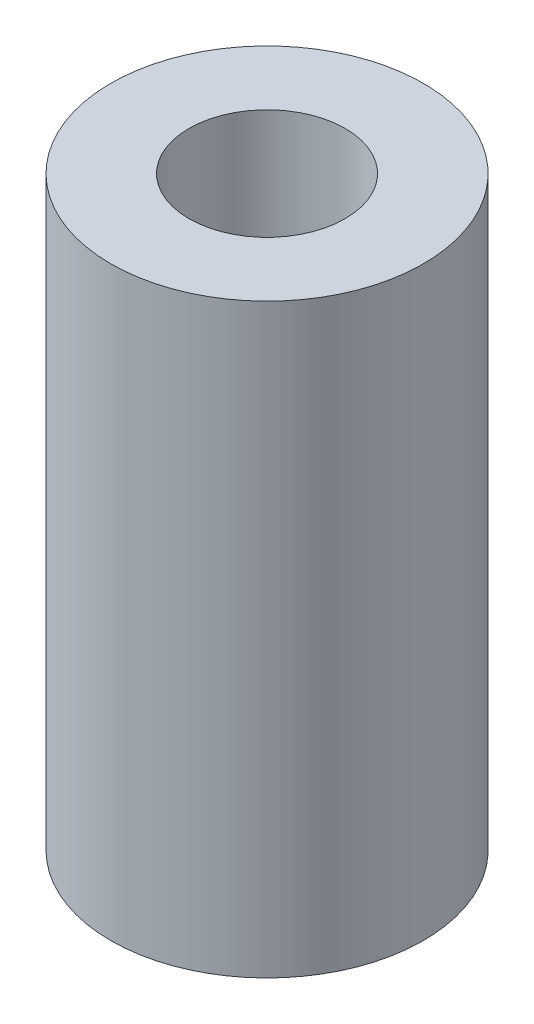
SolidWorks part; units mm, degrees
ref_plane "Front Plane" through (0, 0, 0) normal (0, 0, 1) x (1, 0, 0)
ref_plane "Top Plane" through (0, 0, 0) normal (0, 1, 0) x (1, 0, 0)
ref_plane "Right Plane" through (0, 0, 0) normal (1, 0, 0) x (0, 0, -1)
sketch "Sketch1" plane through (0, 0, 0) normal (0, 1, 0) x (1, 0, 0)
  circle A0 centre (0, 0) radius 6.35
  dimension "D1" = 12.7
extrude "Boss-Extrude1" add sketch "Sketch1" along normal blind 23.8125
sketch "Sketch2" plane through (0, 23.8125, 0) normal (0, 1, 0) x (1, 0, 0)
  circle A0 centre (0, 0) radius 3.175
  dimension "D1" = 6.35
extrude "Cut-Extrude1" cut sketch "Sketch2" against normal through all both and the other way through all
